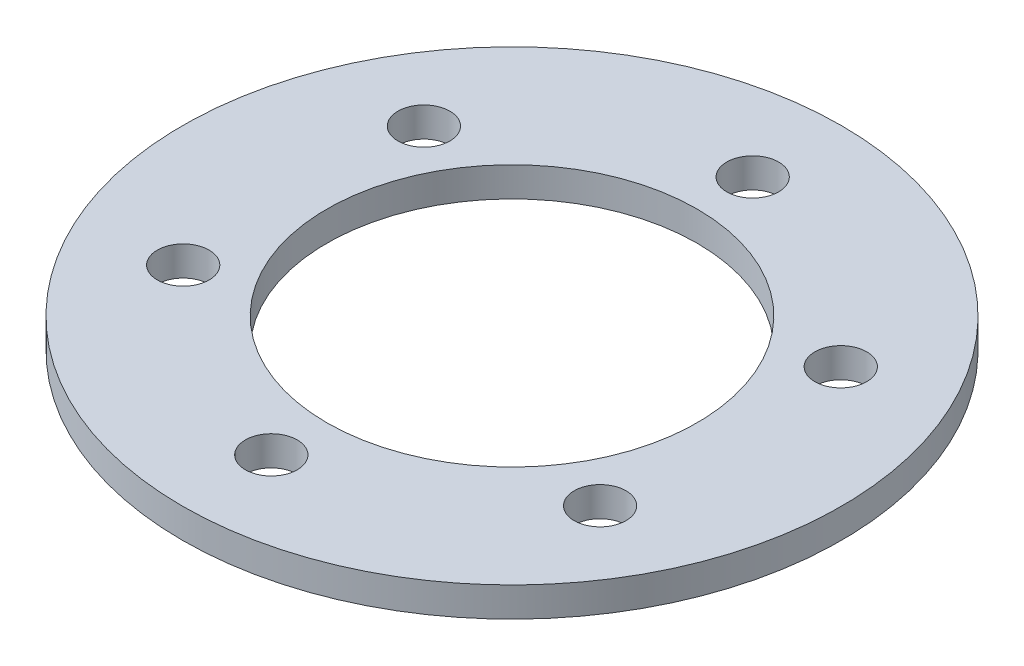
SolidWorks part; units mm, degrees
ref_plane "Front Plane" through (0, 0, 0) normal (0, 0, 1) x (1, 0, 0)
ref_plane "Top Plane" through (0, 0, 0) normal (0, 1, 0) x (1, 0, 0)
ref_plane "Right Plane" through (0, 0, 0) normal (1, 0, 0) x (0, 0, -1)
sketch "Sketch1" plane through (0, 0, 0) normal (0, 1, 0) x (1, 0, 0)
  circle A0 centre (0, 0) radius 22.25
  circle A1 centre (0, 0) radius 16.25 construction
  circle A2 centre (0, 0) radius 12.5
  circle A3 centre (0, 16.25) radius 1.75
  circle A4 centre (14.0729, 8.125) radius 1.75
  circle A5 centre (14.0729, -8.125) radius 1.75
  circle A6 centre (0, -16.25) radius 1.75
  circle A7 centre (-14.0729, -8.125) radius 1.75
  circle A8 centre (-14.0729, 8.125) radius 1.75
  point P8 (0, 0)
  point P9 (14.0728, 8.125)
  point P19 (0, 0)
  point P20 (14.4985, 7.3388)
  point P21 (0, 0)
  dimension "D1" = 44.5
  dimension "D2" = 32.5
  dimension "D3" = 25
  dimension "D4" = 3.5
  dimension "D5" = 6
extrude "Boss-Extrude1" add sketch "Sketch1" along normal blind 2
